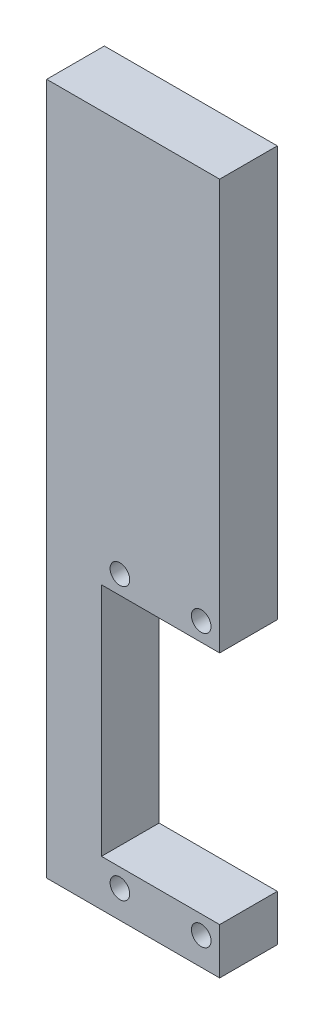
SolidWorks part; units mm, degrees
ref_plane "Front Plane" through (0, 0, 0) normal (0, 0, 1) x (1, 0, 0)
ref_plane "Top Plane" through (0, 0, 0) normal (0, 1, 0) x (1, 0, 0)
ref_plane "Right Plane" through (0, 0, 0) normal (1, 0, 0) x (0, 0, -1)
sketch "Sketch2" plane through (0, 0, 0) normal (0, 0, 1) x (1, 0, 0)
  line L1 (-30.9917, 52.1901) -> (-0.9917, 52.1901)
  line L2 (-30.9917, 52.1901) -> (-30.9917, -67.8099)
  line L3 (-30.9917, -67.8099) -> (-0.9917, -67.8099)
  line L4 (-0.9917, 52.1901) -> (-0.9917, -67.8099)
  dimension "D1" = 120
  dimension "D2" = 30
extrude "Boss-Extrude1" add sketch "Sketch2" along normal blind 10
sketch "Sketch3" plane through (0, 0, 0) normal (0, 0, 1) x (1, 0, 0)
  line L0 (-21.4917, -39.3862) -> (-0.9917, -39.3862) construction
  line L1 (-0.9917, -18.9862) -> (-0.9917, -59.7862)
  line L3 (-0.9917, -67.8099) -> (-0.9917, 52.1901) construction
  line L4 (-21.4917, -59.7862) -> (-21.4917, -62.9862) construction
  line L7 (-0.9917, -59.7862) -> (-21.4917, -59.7862)
  line L9 (-21.4917, -62.9862) -> (-18.2917, -62.9862) construction
  line L10 (-0.9917, -59.7862) -> (-0.9917, -62.9862) construction
  line L11 (-0.9917, -62.9862) -> (-4.1917, -62.9862) construction
  line L12 (-21.4917, -18.9862) -> (-21.4917, -59.7862)
  line L13 (-21.4917, -18.9862) -> (-0.9917, -18.9862)
  line L14 (-0.9917, -18.9862) -> (-0.9917, -59.7862)
  circle A0 centre (-18.2917, -62.9862) radius 1.7
  circle A1 centre (-4.1917, -62.9862) radius 1.7
  circle A2 centre (-4.1917, -15.7862) radius 1.7
  circle A3 centre (-18.2917, -15.7862) radius 1.7
  dimension "D1" = 40.8
  dimension "D2" = 20.5
extrude "Cut-Extrude3" cut sketch "Sketch3" along normal through all contours A1 | A0 | A2 | L13 L1 L7 L12 | A3
